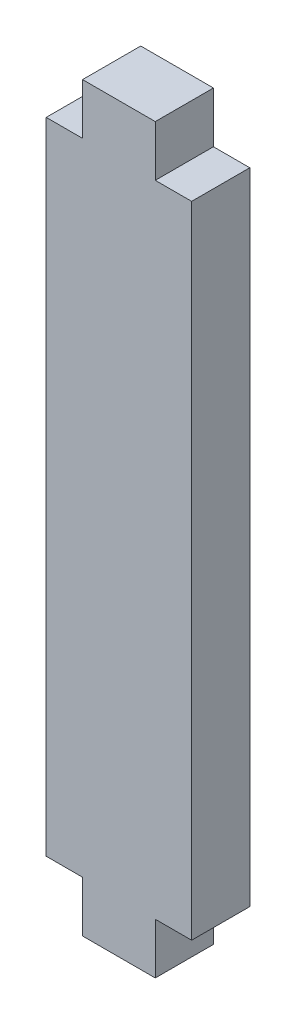
SolidWorks part; units mm, degrees
ref_plane "Front Plane" through (0, 0, 0) normal (0, 0, 1) x (1, 0, 0)
ref_plane "Top Plane" through (0, 0, 0) normal (0, 1, 0) x (1, 0, 0)
ref_plane "Right Plane" through (0, 0, 0) normal (1, 0, 0) x (0, 0, -1)
sketch "Sketch1" plane through (0, 0, 0) normal (0, 0, 1) x (1, 0, 0)
  line L0 (2.5, 22) -> (2.5, 25.5)
  line L1 (-5, -22) -> (-2.5, -22)
  line L2 (-5, -22) -> (-5, 22)
  line L3 (-5, 22) -> (-2.5, 22)
  line L4 (5, -22) -> (5, 22)
  line L5 (-5, -22) -> (5, 22) construction
  line L6 (-5, 22) -> (5, -22) construction
  line L7 (2.5, 25.5) -> (-2.5, 25.5)
  line L8 (-2.5, 25.5) -> (-2.5, 22)
  line L9 (0, 28.9142) -> (0, 49.022) construction
  line L13 (2.5, 22) -> (5, 22)
  line L15 (0, 0) -> (10.2051, 0) construction
  line L16 (2.5, -25.5) -> (-2.5, -25.5)
  line L17 (-2.5, -25.5) -> (-2.5, -22)
  line L18 (2.5, -22) -> (2.5, -25.5)
  line L19 (2.5, -22) -> (5, -22)
  point P0 (0, 0)
  point P12 (0, 25.5)
  dimension "D1" = 10
  dimension "D2" = 44
  dimension "D3" = 5
  dimension "D4" = 3.5
extrude "Boss-Extrude1" add sketch "Sketch1" along normal blind 4
